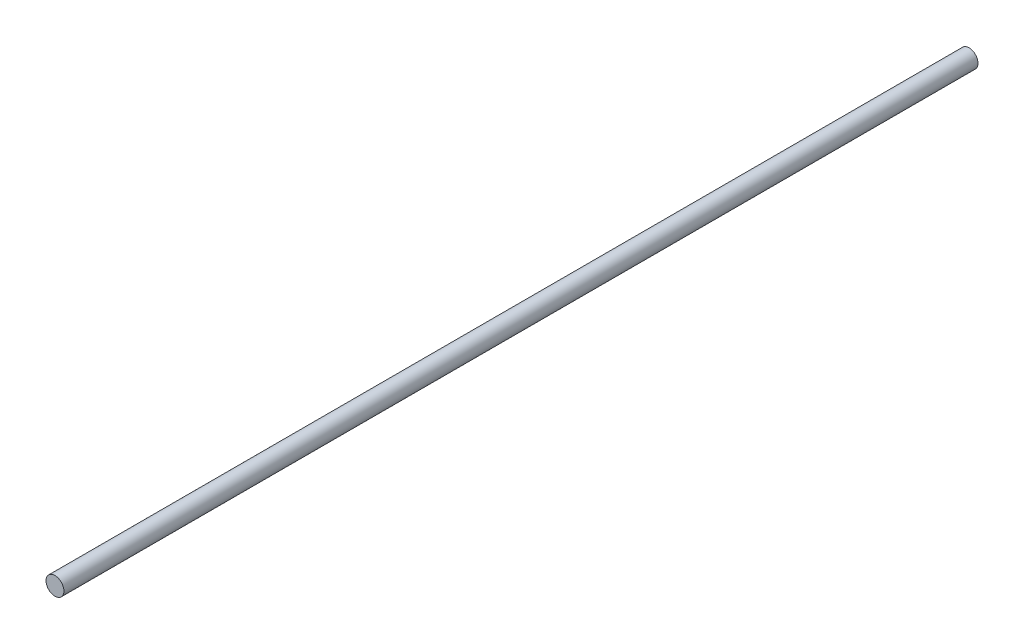
SolidWorks part; units mm, degrees
ref_plane "Front Plane" through (0, 0, 0) normal (0, 0, 1) x (1, 0, 0)
ref_plane "Top Plane" through (0, 0, 0) normal (0, 1, 0) x (1, 0, 0)
ref_plane "Right Plane" through (0, 0, 0) normal (1, 0, 0) x (0, 0, -1)
sketch "Sketch2" plane through (0, 0, 0) normal (0, 0, 1) x (-0.8405, -0.5419, 0)
  circle A0 centre (-224.0802, 95.2464) radius 5
extrude "Boss-Extrude1" add sketch "Sketch2" along normal blind 510
